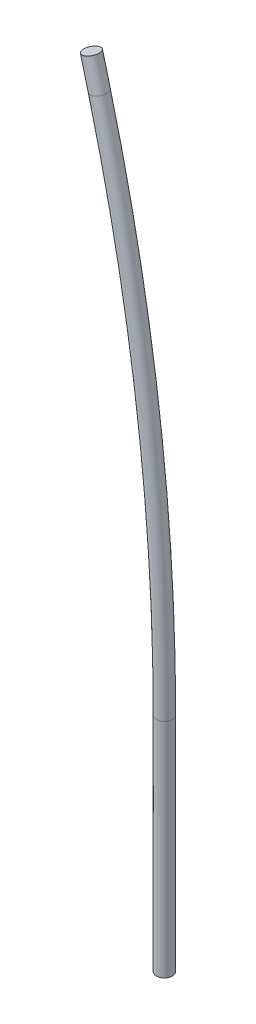
SolidWorks part; units mm, degrees
material "Nylon 101"
ref_plane "Front Plane" through (0, 0, 0) normal (0, 0, 1) x (1, 0, 0)
ref_plane "Top Plane" through (0, 0, 0) normal (0, 1, 0) x (1, 0, 0)
ref_plane "Right Plane" through (0, 0, 0) normal (1, 0, 0) x (0, 0, -1)
sketch "Sketch1" plane through (0, 0, 0) normal (0, 0, 1) x (1, 0, 0)
  line L0 (41.275, 0) -> (41.275, -18.7688) construction
  line L1 (0, 0) -> (0, 136.5906) construction
  arc A0 (41.275, 0) -> (15.24, 203.2) centre (-764.7181, 0) ccw
  dimension "D1" = 41.275
  dimension "D2" = 15.24
  dimension "D3" = 203.2
sketch "Sketch2" plane through (0, 0, 0) normal (0, 1, 0) x (1, 0, 0)
  line L0 (15.24, 0) -> (41.275, 0) construction
  circle A0 centre (41.275, 0) radius 3.175
  point P4 (48.8815, 0)
  point P5 (41.275, 0)
  point P6 (46.706, 0)
  dimension "D1" = 6.35
  dimension "D2" = 41.275
sweep "Sweep1" add profiles "Sketch2" path "Sketch1"
sketch "Sketch4" plane through (-48.6056, 186.5665, 0) normal (-0.2521, 0.9677, 0) x (0.9677, 0.2521, 0)
  circle A0 centre (65.9767, 0) radius 3.175
  dimension "D1" = 6.35
  dimension "D2" = 65.9767
extrude "Boss-Extrude1" add sketch "Sketch4" along normal blind 12.7
sketch "Sketch5" plane through (0, 0, 0) normal (0, -1, 0) x (1, 0, 0)
  circle A0 centre (41.275, 0) radius 3.175
  dimension "D2" = 6.35
  dimension "D1" = 41.275
extrude "Boss-Extrude2" add sketch "Sketch5" along normal blind 88.9
